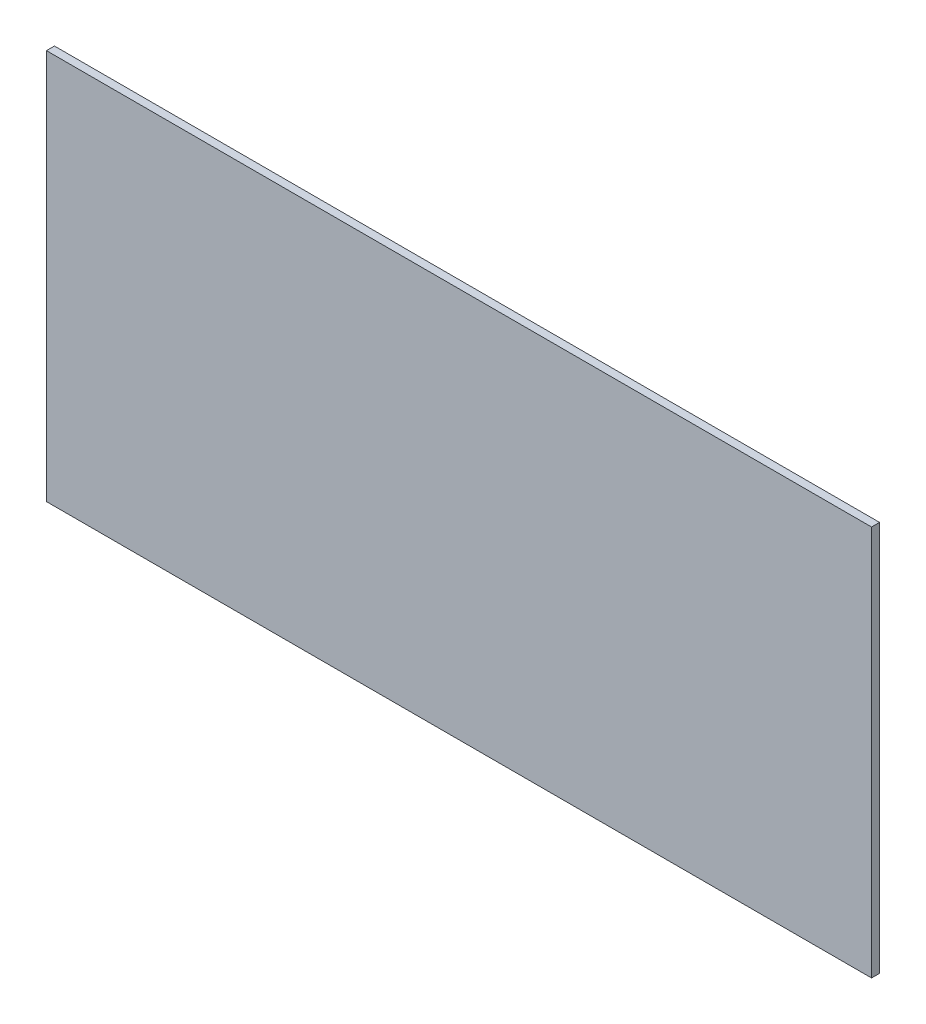
SolidWorks part; units mm, degrees
material "ABS PC"
ref_plane "Front Plane" through (0, 0, 0) normal (0, 0, 1) x (1, 0, 0)
ref_plane "Top Plane" through (0, 0, 0) normal (0, 1, 0) x (1, 0, 0)
ref_plane "Right Plane" through (0, 0, 0) normal (1, 0, 0) x (0, 0, -1)
sketch "Sketch1" plane through (0, 0, 0) normal (0, 0, 1) x (1, 0, 0)
  line L0 (-9.766, 30.1104) -> (155.234, 30.1104)
  line L1 (155.234, 30.1104) -> (155.234, -47.9921)
  line L2 (155.234, -47.9921) -> (-9.766, -47.9921)
  line L3 (-9.766, -47.9921) -> (-9.766, 30.1104)
  dimension "D1" = 78.1025
  dimension "D2" = 165
extrude "Boss-Extrude1" add sketch "Sketch1" along normal blind 1.6
